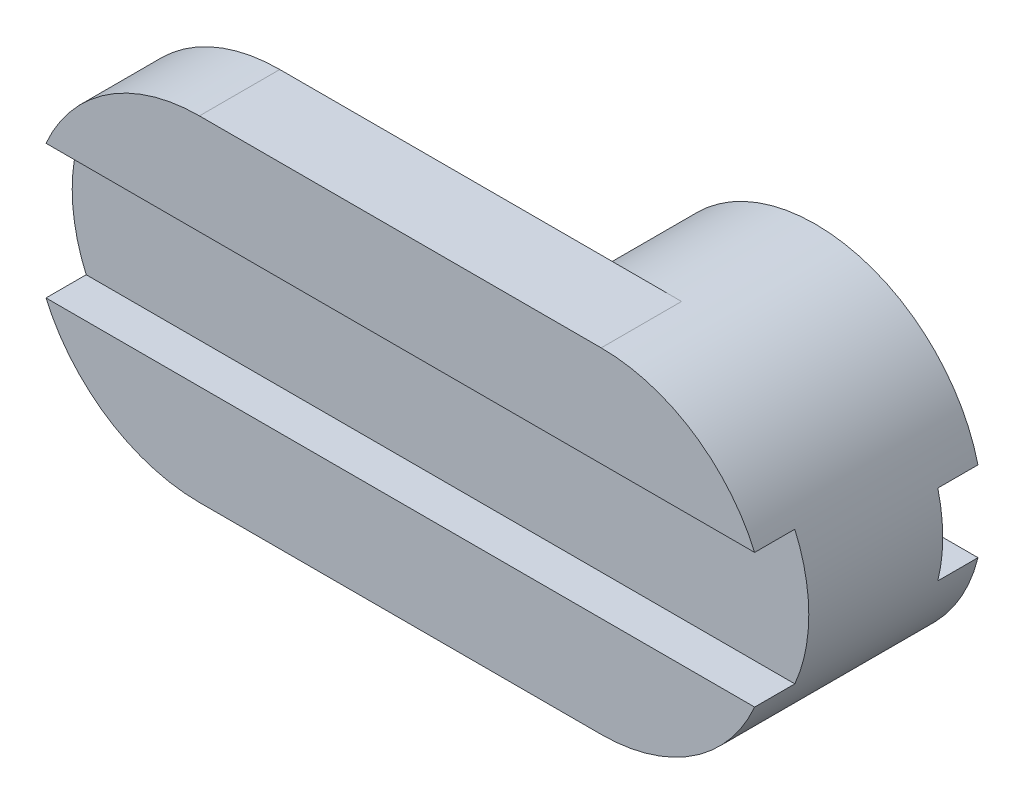
SolidWorks part; units mm, degrees
ref_plane "Front Plane" through (0, 0, 0) normal (0, 0, 1) x (1, 0, 0)
ref_plane "Top Plane" through (0, 0, 0) normal (0, 1, 0) x (1, 0, 0)
ref_plane "Right Plane" through (0, 0, 0) normal (1, 0, 0) x (0, 0, -1)
sketch "Sketch1" plane through (0, 0, 0) normal (0, 0, 1) x (1, 0, 0)
  line L1 (30, -25) -> (-30, -25)
  line L3 (30, 25) -> (-30, 25)
  line L6 (5.4098, 4.5082) -> (0, 0) construction
  arc A0 (30, -25) -> (30, 25) centre (30, 0) ccw
  arc A1 (-30, 25) -> (-30, -25) centre (-30, 0) ccw
  point P0 (0, 0)
  dimension "D2" = 25
  dimension "D1" = 60
extrude "Boss-Extrude1" add sketch "Sketch1" along normal blind 12
sketch "Sketch2" plane through (0, 0, 12) normal (0, 0, 1) x (1, 0, 0)
  line L1 (57.6845, -10) -> (-57.6845, -10)
  line L2 (57.6845, -10) -> (57.6845, 10)
  line L3 (57.6845, 10) -> (-57.6845, 10)
  line L4 (-57.6845, -10) -> (-57.6845, 10)
  line L5 (57.6845, -10) -> (-57.6845, 10) construction
  line L6 (57.6845, 10) -> (-57.6845, -10) construction
  point P0 (0, 0)
  dimension "D1" = 20
extrude "Cut-Extrude1" cut sketch "Sketch2" against normal blind 6
sketch "Sketch3" plane through (0, 0, 0) normal (0, 0, -1) x (-1, 0, 0)
  circle A0 centre (-30, 0) radius 25
  circle A1 centre (-30, 0) radius 10
  dimension "D1" = 20
extrude "Boss-Extrude2" add sketch "Sketch3" along normal blind 20
sketch "Sketch4" plane through (0, 0, -20) normal (0, 0, -1) x (-1, 0, 0)
  line L0 (0, 0) -> (-64.7386, 0) construction
  line L1 (-55, -6) -> (-55, 6)
  line L2 (-5, -6) -> (-5, 6)
  line L3 (-55, 6) -> (-5, 6)
  line L4 (-55, -6) -> (-5, -6)
  circle A0 centre (-30, 0) radius 25 construction
  arc A1 (-30, -25) -> (-30, 25) centre (-30, 0) ccw construction
  point P13 (-5, 0)
  point P14 (-55, 0)
  dimension "D1" = 6
extrude "Cut-Extrude2" cut sketch "Sketch4" against normal blind 6
sketch "Sketch5" plane through (0, 0, 0) normal (0, 0, -1) x (-1, 0, 0)
  line L0 (18, 0) -> (30, 0) construction
  line L1 (18, 12) -> (30, 12)
  line L2 (18, -12) -> (30, -12)
  line L3 (18, 0) -> (30, 0) construction
  line L4 (18, 6) -> (30, 6)
  line L5 (18, -6) -> (30, -6)
  arc A0 (18, 12) -> (18, -12) centre (18, 0) ccw
  arc A1 (30, -12) -> (30, 12) centre (30, 0) ccw
  arc A2 (18, 6) -> (18, -6) centre (18, 0) ccw
  arc A3 (30, -6) -> (30, 6) centre (30, 0) ccw
  point P2 (24, 0)
  point P10 (24, 0)
  dimension "D1" = 12
  dimension "D2" = 6
  dimension "D3" = 6
extrude "Boss-Extrude3" add sketch "Sketch5" along normal blind 4
